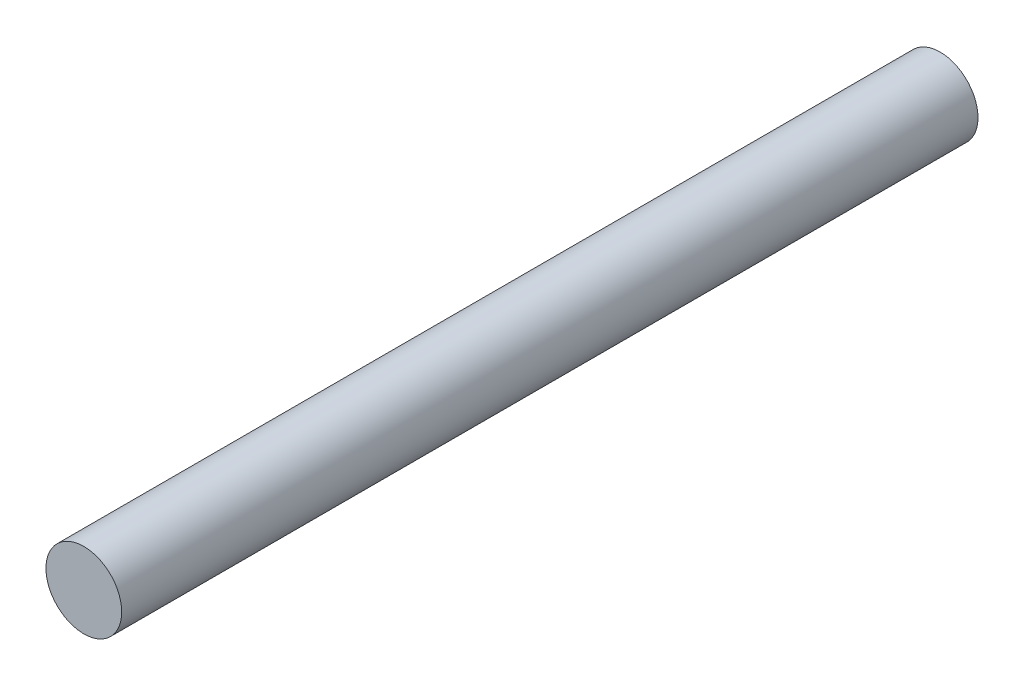
SolidWorks part; units mm, degrees
ref_plane "正面" through (0, 0, 0) normal (0, 0, 1) x (1, 0, 0)
ref_plane "平面" through (0, 0, 0) normal (0, 1, 0) x (1, 0, 0)
ref_plane "右側面" through (0, 0, 0) normal (1, 0, 0) x (0, 0, -1)
sketch "ｽｹｯﾁ1" plane through (0, 0, 0) normal (0, 0, 1) x (1, 0, 0)
  circle A0 centre (0, 0) radius 5
  dimension "D1" = 10
extrude "ﾎﾞｽ - 押し出し1" add sketch "ｽｹｯﾁ1" along normal blind 113
